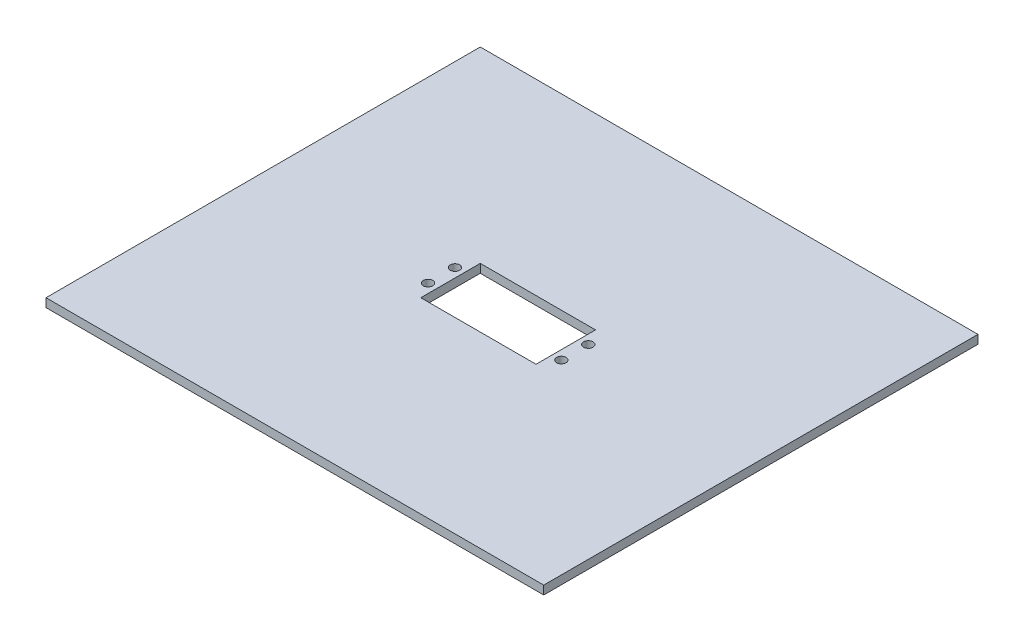
SolidWorks part; units mm, degrees
ref_plane "Front Plane" through (0, 0, 0) normal (0, 0, 1) x (1, 0, 0)
ref_plane "Top Plane" through (0, 0, 0) normal (0, 1, 0) x (1, 0, 0)
ref_plane "Right Plane" through (0, 0, 0) normal (1, 0, 0) x (0, 0, -1)
sketch "Sketch1" plane through (0, 0, 0) normal (0, 1, 0) x (1, 0, 0)
  line L0 (0, 0) -> (-35, 0) construction
  line L1 (-10.05, 10.05) -> (-10.05, -10.05) construction
  line L2 (30.75, -10.05) -> (-10.05, -10.05) construction
  line L3 (30.75, 10.05) -> (30.75, -10.05) construction
  line L4 (30.75, 10.05) -> (-10.05, 10.05) construction
  line L5 (-10.05, 10.05) -> (-10.05, -10.05) construction
  line L6 (30.75, -10.05) -> (-10.05, -10.05) construction
  line L7 (30.75, 10.05) -> (30.75, -10.05) construction
  line L8 (30.75, 10.05) -> (-10.05, 10.05) construction
  line L9 (31.75, 11.05) -> (-11.05, 11.05)
  line L10 (-11.05, 11.05) -> (-11.05, -11.05)
  line L11 (31.75, -11.05) -> (-11.05, -11.05)
  line L12 (31.75, 11.05) -> (31.75, -11.05)
  line L13 (-80.6396, -80.6396) -> (104.2, -80.6396) construction
  line L14 (-80.6396, 80.6396) -> (104.2, 80.6396) construction
  line L15 (-80.6396, -80.6396) -> (104.2, -80.6396)
  line L16 (-80.6396, 80.6396) -> (104.2, 80.6396)
  line L17 (104.2, -80.6396) -> (104.2, 80.6396)
  line L18 (-80.6396, 80.6396) -> (-80.6396, -80.6396)
  circle A0 centre (0, 0) radius 35 construction
  circle A1 centre (0, 0) radius 35 construction
  circle A2 centre (-14.4, 5) radius 1.75 construction
  circle A3 centre (-14.4, -5) radius 1.75 construction
  circle A4 centre (35.1, -5) radius 1.75 construction
  circle A5 centre (35.1, 5) radius 1.75 construction
  circle A6 centre (-14.4, 5) radius 1.75
  circle A7 centre (-14.4, -5) radius 1.75
  circle A8 centre (35.1, -5) radius 1.75
  circle A9 centre (35.1, 5) radius 1.75
  dimension "D1" = 1
extrude "Boss-Extrude1" add sketch "Sketch1" against normal up to vertex (3.2 mm away)
